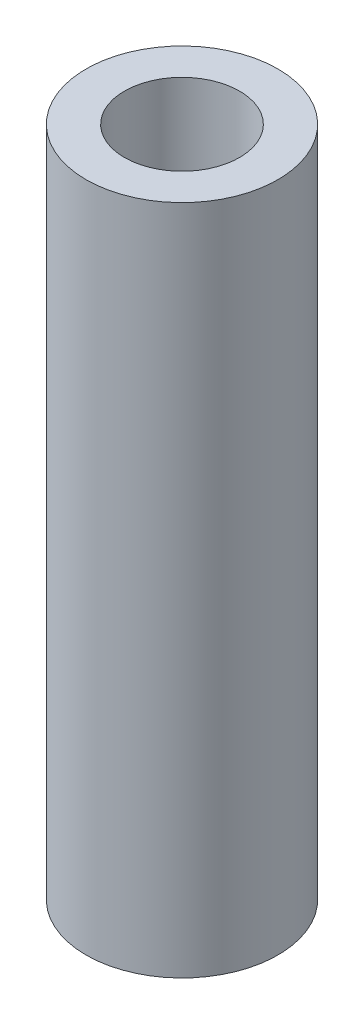
SolidWorks part; units mm, degrees
ref_plane "前视基准面" through (0, 0, 0) normal (0, 0, 1) x (1, 0, 0)
ref_plane "上视基准面" through (0, 0, 0) normal (0, 1, 0) x (1, 0, 0)
ref_plane "右视基准面" through (0, 0, 0) normal (1, 0, 0) x (0, 0, -1)
sketch "Sketch1" plane through (0, 0, 0) normal (0, 1, 0) x (1, 0, 0)
  circle A0 centre (0, 0) radius 3
  circle A1 centre (0, 0) radius 5
extrude "Boss-Extrude1" add sketch "Sketch1" along normal blind 35
